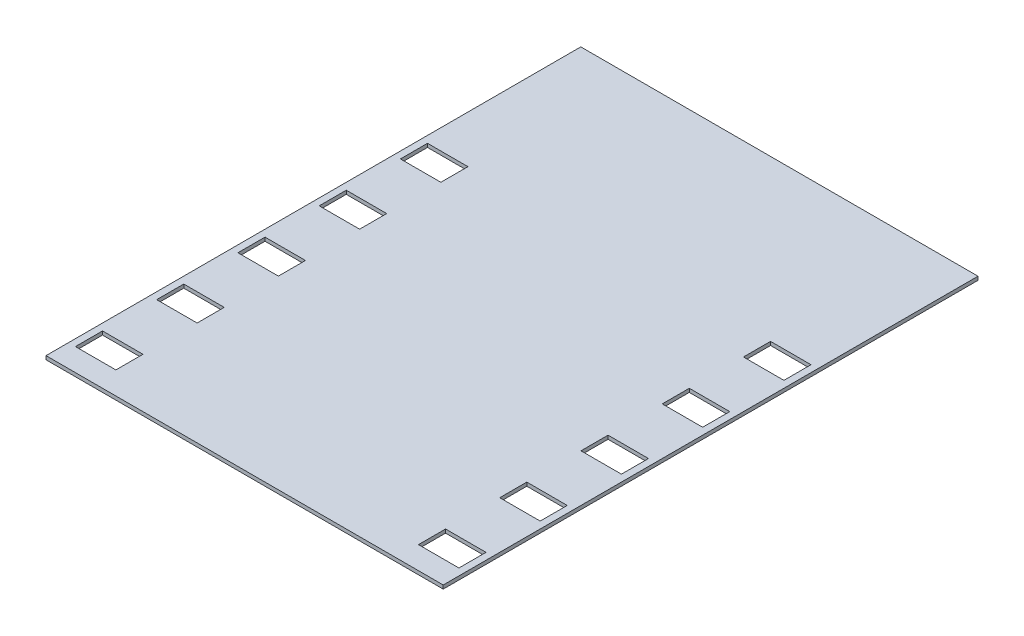
SolidWorks part; units mm, degrees
ref_plane "Front Plane" through (0, 0, 0) normal (0, 0, 1) x (1, 0, 0)
ref_plane "Top Plane" through (0, 0, 0) normal (0, 1, 0) x (1, 0, 0)
ref_plane "Right Plane" through (0, 0, 0) normal (1, 0, 0) x (0, 0, -1)
sketch "Sketch1" plane through (0, 0, 0) normal (0, 1, 0) x (1, 0, 0)
  line L1 (-139.7, -188.087) -> (139.7, -188.087)
  line L2 (-139.7, -188.087) -> (-139.7, 188.087)
  line L3 (-139.7, 188.087) -> (139.7, 188.087)
  line L4 (139.7, -188.087) -> (139.7, 188.087)
  line L5 (-139.7, -188.087) -> (139.7, 188.087) construction
  line L6 (-139.7, 188.087) -> (139.7, -188.087) construction
  point P0 (0, 0)
  dimension "D1" = 279.4
  dimension "D2" = 376.174
extrude "Boss-Extrude1" add sketch "Sketch1" along normal blind 2.54
sketch "Sketch2" plane through (0, 2.54, 0) normal (0, 1, 0) x (1, 0, 0)
  line L0 (-120.65, 188.087) -> (-120.65, -188.087) construction
  line L1 (139.7, 188.087) -> (-139.7, 188.087) construction
  line L2 (-139.7, -188.087) -> (139.7, -188.087) construction
  line L3 (-134.874, -115.062) -> (-106.426, -115.062)
  line L4 (-134.874, -172.212) -> (-106.426, -172.212)
  line L5 (-134.874, -172.212) -> (-134.874, -153.162)
  line L6 (-134.874, -153.162) -> (-106.426, -153.162)
  line L7 (-106.426, -172.212) -> (-106.426, -153.162)
  line L8 (-134.874, -172.212) -> (-106.426, -153.162) construction
  line L9 (-134.874, -153.162) -> (-106.426, -172.212) construction
  line L10 (-134.874, -115.062) -> (-134.874, -96.012)
  line L11 (-134.874, -96.012) -> (-106.426, -96.012)
  line L12 (-106.426, -115.062) -> (-106.426, -96.012)
  line L13 (-134.874, -115.062) -> (-106.426, -96.012) construction
  line L14 (-134.874, -96.012) -> (-106.426, -115.062) construction
  line L15 (-134.874, -57.912) -> (-106.426, -57.912)
  line L16 (-134.874, -57.912) -> (-134.874, -38.862)
  line L17 (-134.874, -38.862) -> (-106.426, -38.862)
  line L18 (-106.426, -57.912) -> (-106.426, -38.862)
  line L19 (-134.874, -57.912) -> (-106.426, -38.862) construction
  line L20 (-134.874, -38.862) -> (-106.426, -57.912) construction
  line L21 (-134.874, -0.762) -> (-106.426, -0.762)
  line L22 (-134.874, -0.762) -> (-134.874, 18.288)
  line L23 (-134.874, 18.288) -> (-106.426, 18.288)
  line L24 (-106.426, -0.762) -> (-106.426, 18.288)
  line L25 (-134.874, -0.762) -> (-106.426, 18.288) construction
  line L26 (-134.874, 18.288) -> (-106.426, -0.762) construction
  line L27 (-134.874, 56.388) -> (-106.426, 56.388)
  line L28 (-134.874, 56.388) -> (-134.874, 75.438)
  line L29 (-134.874, 75.438) -> (-106.426, 75.438)
  line L30 (-106.426, 56.388) -> (-106.426, 75.438)
  line L31 (-134.874, 56.388) -> (-106.426, 75.438) construction
  line L32 (-134.874, 75.438) -> (-106.426, 56.388) construction
  line L33 (0, 188.087) -> (0, -188.087) construction
  line L34 (134.874, 75.438) -> (106.426, 56.388) construction
  line L35 (134.874, 56.388) -> (106.426, 75.438) construction
  line L36 (134.874, 18.288) -> (106.426, -0.762) construction
  line L37 (134.874, -0.762) -> (106.426, 18.288) construction
  line L38 (134.874, -38.862) -> (106.426, -57.912) construction
  line L39 (134.874, -57.912) -> (106.426, -38.862) construction
  line L40 (134.874, -96.012) -> (106.426, -115.062) construction
  line L41 (134.874, -115.062) -> (106.426, -96.012) construction
  line L42 (134.874, -153.162) -> (106.426, -172.212) construction
  line L43 (134.874, -172.212) -> (106.426, -153.162) construction
  line L44 (120.65, 188.087) -> (120.65, -188.087) construction
  line L45 (106.426, 56.388) -> (106.426, 75.438)
  line L46 (134.874, 75.438) -> (106.426, 75.438)
  line L47 (134.874, 56.388) -> (134.874, 75.438)
  line L48 (134.874, 56.388) -> (106.426, 56.388)
  line L49 (106.426, -0.762) -> (106.426, 18.288)
  line L50 (134.874, 18.288) -> (106.426, 18.288)
  line L51 (134.874, -0.762) -> (134.874, 18.288)
  line L52 (134.874, -0.762) -> (106.426, -0.762)
  line L53 (106.426, -57.912) -> (106.426, -38.862)
  line L54 (134.874, -38.862) -> (106.426, -38.862)
  line L55 (134.874, -57.912) -> (134.874, -38.862)
  line L56 (134.874, -57.912) -> (106.426, -57.912)
  line L57 (106.426, -115.062) -> (106.426, -96.012)
  line L58 (134.874, -96.012) -> (106.426, -96.012)
  line L59 (134.874, -115.062) -> (134.874, -96.012)
  line L60 (106.426, -172.212) -> (106.426, -153.162)
  line L61 (134.874, -153.162) -> (106.426, -153.162)
  line L62 (134.874, -172.212) -> (134.874, -153.162)
  line L63 (134.874, -172.212) -> (106.426, -172.212)
  line L64 (134.874, -115.062) -> (106.426, -115.062)
  line L65 (-139.7, 188.087) -> (-139.7, -188.087) construction
  point P6 (-120.65, -162.687)
  point P13 (-120.65, -105.537)
  point P18 (-120.65, -48.387)
  point P23 (-120.65, 8.763)
  point P28 (-120.65, 65.913)
  point P55 (120.65, 65.913)
  point P56 (120.65, 8.763)
  point P57 (120.65, -48.387)
  point P58 (120.65, -105.537)
  point P59 (120.65, -162.687)
  dimension "D1" = 28.448
  dimension "D2" = 25.4
  dimension "D3" = 19.05
  dimension "D5" = 4.826
  dimension "D4" = 5
extrude "Cut-Extrude1" cut sketch "Sketch2" against normal through all
